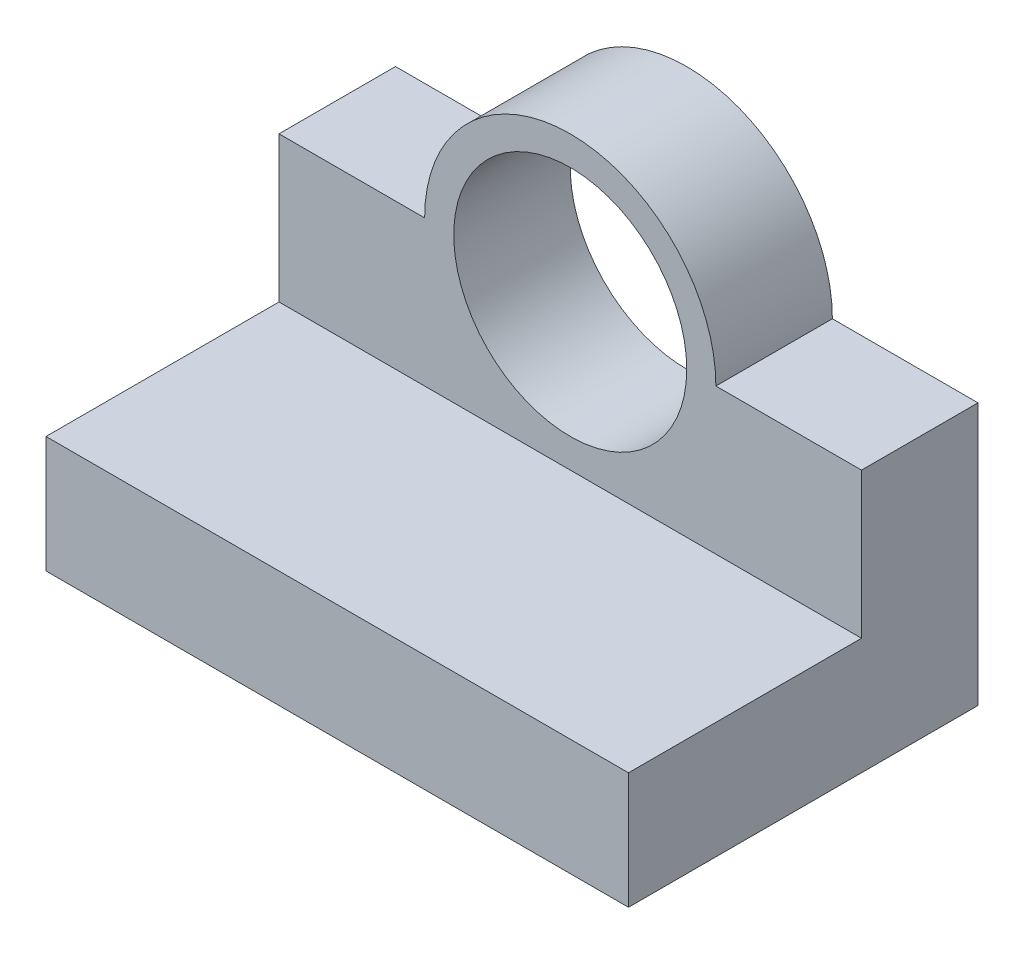
SolidWorks part; units mm, degrees
ref_plane "Front Plane" through (0, 0, 0) normal (0, 0, 1) x (1, 0, 0)
ref_plane "Top Plane" through (0, 0, 0) normal (0, 1, 0) x (1, 0, 0)
ref_plane "Right Plane" through (0, 0, 0) normal (1, 0, 0) x (0, 0, -1)
sketch "Sketch1" plane through (0, 0, 0) normal (0, 0, 1) x (1, 0, 0)
  line L0 (25, 45) -> (50, 45)
  line L1 (-50, 0) -> (50, 0)
  line L2 (-50, 0) -> (-50, 45)
  line L3 (-50, 45) -> (-25, 45)
  line L4 (50, 0) -> (50, 45)
  arc A0 (25, 45) -> (-25, 45) centre (0, 45) ccw
  circle A1 centre (0, 45) radius 20
  point P4 (0, 0)
  dimension "D4" = 25
  dimension "D5" = 40
  dimension "D1" = 45
  dimension "D2" = 100
  dimension "D3" = 50
extrude "Boss-Extrude1" add sketch "Sketch1" along normal mid plane 20
sketch "Sketch2" plane through (0, 0, 10) normal (0, 0, 1) x (1, 0, 0)
  line L0 (50, 0) -> (50, 45) construction
  line L1 (-50, 0) -> (50, 0)
  line L2 (-50, 0) -> (-50, 20)
  line L3 (-50, 20) -> (50, 20)
  line L4 (50, 0) -> (50, 20)
  dimension "D1" = 20
extrude "Boss-Extrude2" add sketch "Sketch2" along normal blind 40
